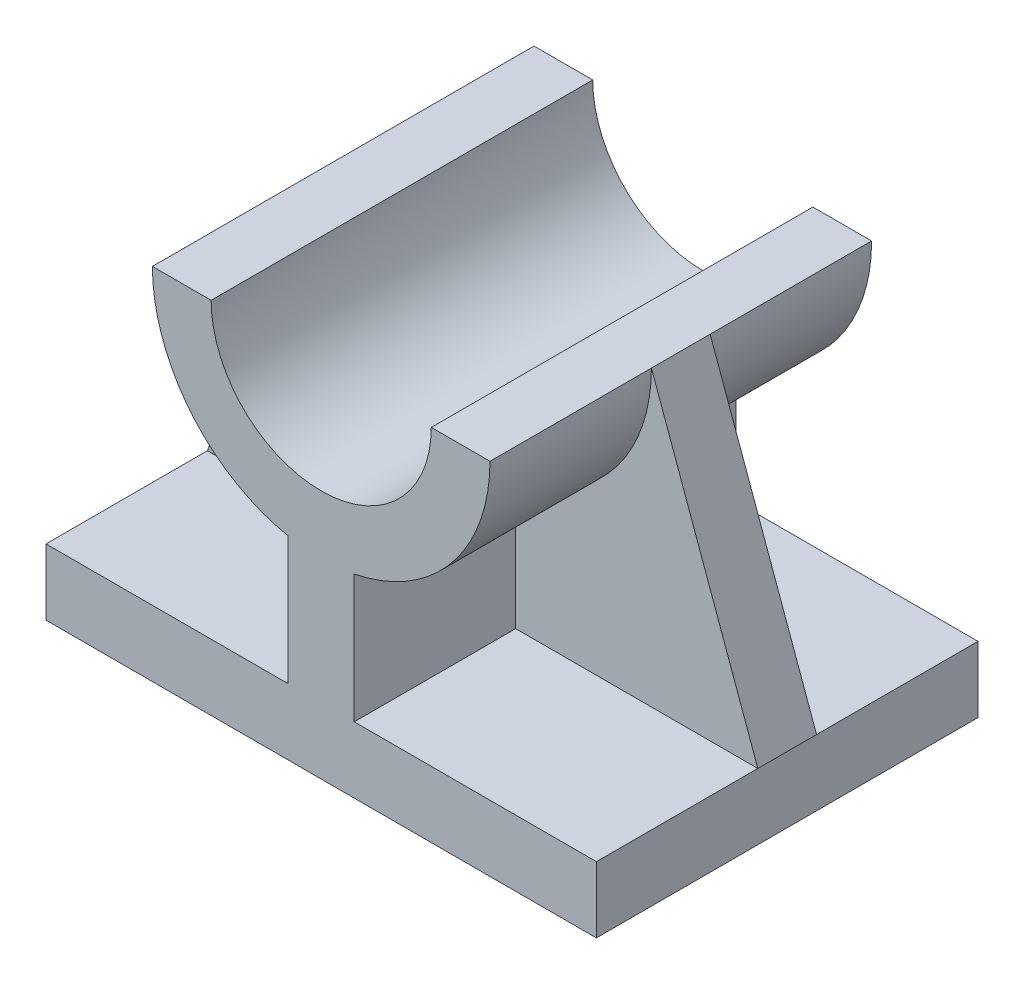
SolidWorks part; units mm, degrees
ref_plane "Front Plane" through (0, 0, 0) normal (0, 0, 1) x (1, 0, 0)
ref_plane "Top Plane" through (0, 0, 0) normal (0, 1, 0) x (1, 0, 0)
ref_plane "Right Plane" through (0, 0, 0) normal (1, 0, 0) x (0, 0, -1)
sketch "Sketch2" plane through (0, 0, 0) normal (0, 0, 1) x (1, 0, 0)
  line L0 (-23, 44.5) -> (-15, 44.5)
  line L1 (-37.5, -4.5) -> (37.5, -4.5)
  line L2 (-37.5, -4.5) -> (-37.5, 4.5)
  line L3 (-37.5, 4.5) -> (-4.5, 4.5)
  line L4 (37.5, -4.5) -> (37.5, 4.5)
  line L5 (-37.5, -4.5) -> (37.5, 4.5) construction
  line L6 (-37.5, 4.5) -> (37.5, -4.5) construction
  line L9 (15, 44.5) -> (23, 44.5)
  line L10 (0, 44.5) -> (0, -35.1728) construction
  line L11 (-4.5, 4.5) -> (-4.5, 21.9445)
  line L12 (4.5, 4.5) -> (4.5, 21.9445)
  line L13 (4.5, 4.5) -> (37.5, 4.5)
  arc A0 (-15, 44.5) -> (15, 44.5) centre (0, 44.5) ccw
  arc A1 (-23, 44.5) -> (-4.5, 21.9445) centre (0, 44.5) ccw
  arc A2 (4.5, 21.9445) -> (23, 44.5) centre (0, 44.5) ccw
  point P0 (0, 0)
  dimension "D3" = 15
  dimension "D4" = 23
  dimension "D1" = 75
  dimension "D2" = 9
  dimension "D5" = 40
  dimension "D6" = 9
extrude "Boss-Extrude1" add sketch "Sketch2" against normal mid plane 52
sketch "Sketch3" plane through (0, 0, 0) normal (0, 0, 1) x (1, 0, 0)
  line L0 (23, 44.5) -> (37.5, 4.5)
rib "Rib1" sketch "Sketch3" sketch "Sketch3" thickness 8 extrusion direction parallel to sketch draft on no parameters "D1"=8
mirror "Mirror1" about plane through (0, 0, 0) normal (1, 0, 0) of "Rib1"
